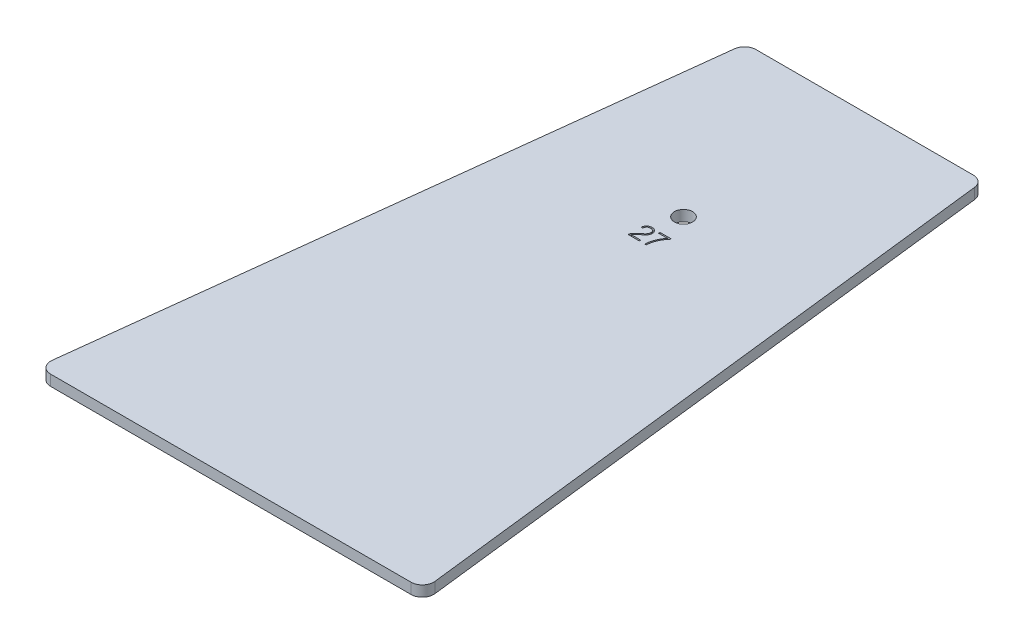
SolidWorks part; units mm, degrees
material "Acrylic (Medium-high impact)"
ref_plane "Front Plane" through (0, 0, 0) normal (0, 0, 1) x (1, 0, 0)
ref_plane "Top Plane" through (0, 0, 0) normal (0, 1, 0) x (1, 0, 0)
ref_plane "Right Plane" through (0, 0, 0) normal (1, 0, 0) x (0, 0, -1)
sketch "Sketch1" plane through (0, 0, 0) normal (0, 1, 0) x (1, 0, 0)
  line L0 (0, 0) -> (0, -355.6) construction
  line L1 (-66.675, 0) -> (66.675, 0)
  line L2 (66.675, 0) -> (108.2387, -355.6)
  line L3 (108.2387, -355.6) -> (-108.2387, -355.6)
  line L4 (-66.675, 0) -> (-108.2387, -355.6)
  dimension "D1" = 355.6
  dimension "D2" = 13.333
  dimension "D3" = 133.35
extrude "Boss-Extrude1" add sketch "Sketch1" along normal blind 5.9944
sketch "Sketch2" plane through (0, 5.9944, 0) normal (0, 1, 0) x (1, 0, 0)
  line L0 (0, 0) -> (0, -101.6) construction
  line L1 (66.675, 0) -> (-66.675, 0) construction
  circle A0 centre (0, -101.6) radius 5.08
  dimension "D2" = 10.16
  dimension "D1" = 101.6
extrude "Cut-Extrude1" cut sketch "Sketch2" against normal through all
sketch "Sketch3" plane through (0, 5.9944, 0) normal (0, 1, 0) x (1, 0, 0)
  line L0 (0, 0) -> (0, -114.3) construction
  line L1 (-7.62, -125.73) -> (7.62, -125.73) construction
  line L2 (-7.62, -125.73) -> (-7.62, -114.3) construction
  line L3 (-7.62, -114.3) -> (7.62, -114.3) construction
  line L4 (7.62, -125.73) -> (7.62, -114.3) construction
  line L5 (66.675, 0) -> (-66.675, 0) construction
  text T0 "27"
  dimension "D1" = 15.24
  dimension "D2" = 114.3
  dimension "D3" = 11.43
extrude "Cut-Extrude2" cut sketch "Sketch3" against normal blind 1.27
fillet "Fillet1" radius 6.35 4 edges at (108.2387, 2.9972, 355.6) (-108.2387, 2.9972, 355.6) (-66.675, 2.9972, 0) (66.675, 2.9972, 0)
